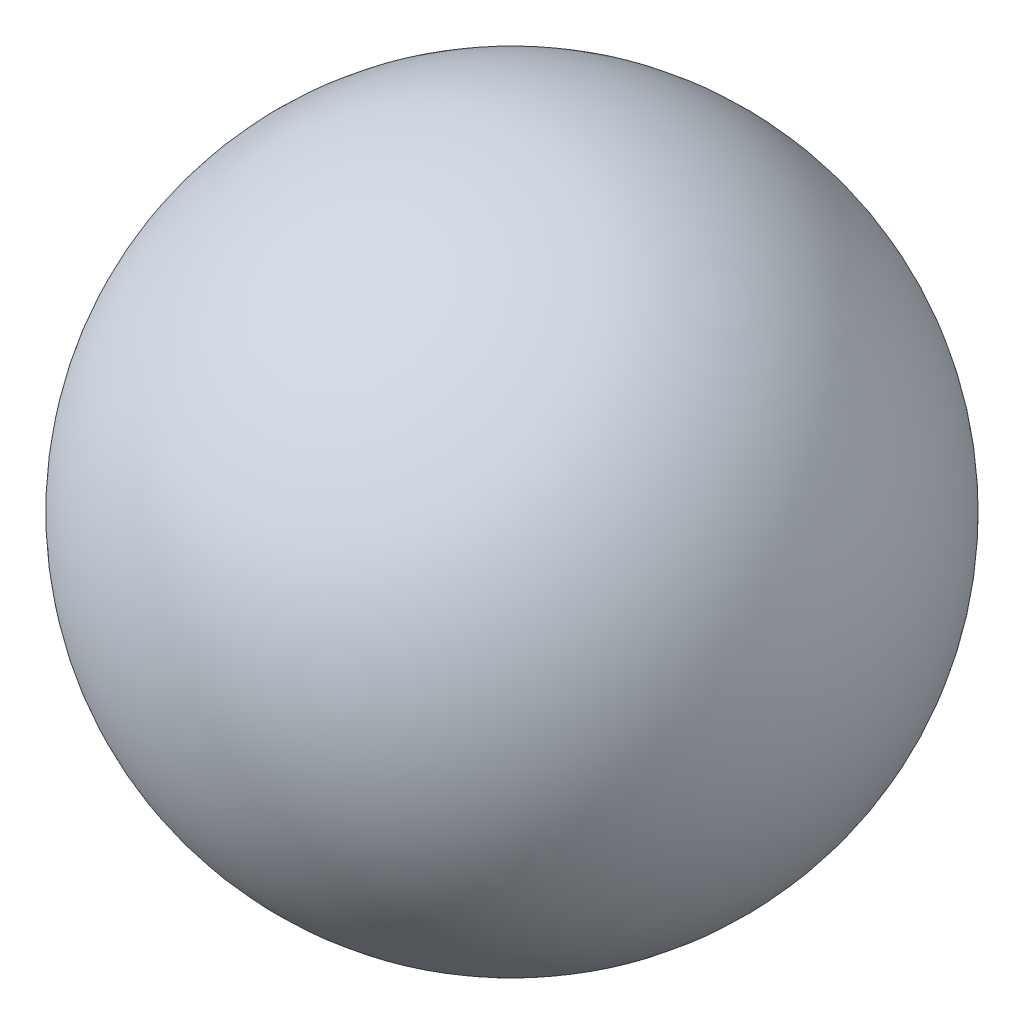
SolidWorks part; units mm, degrees
ref_plane "Front Plane" through (0, 0, 0) normal (0, 0, 1) x (1, 0, 0)
ref_plane "Top Plane" through (0, 0, 0) normal (0, 1, 0) x (1, 0, 0)
ref_plane "Right Plane" through (0, 0, 0) normal (1, 0, 0) x (0, 0, -1)
sketch "Sketch2" plane through (0, 0, 0) normal (0, 0, 1) x (1, 0, 0)
  line L0 (0, -18.5) -> (0, 18.5)
  line L2 (0, 0) -> (-18.5, 0)
  arc A0 (0, 18.5) -> (0, -18.5) centre (0, 0) ccw
  point P4 (0, 0)
  dimension "D1" = 37
revolve "Revolve1" add sketch "Sketch2" angle 360 about L0
